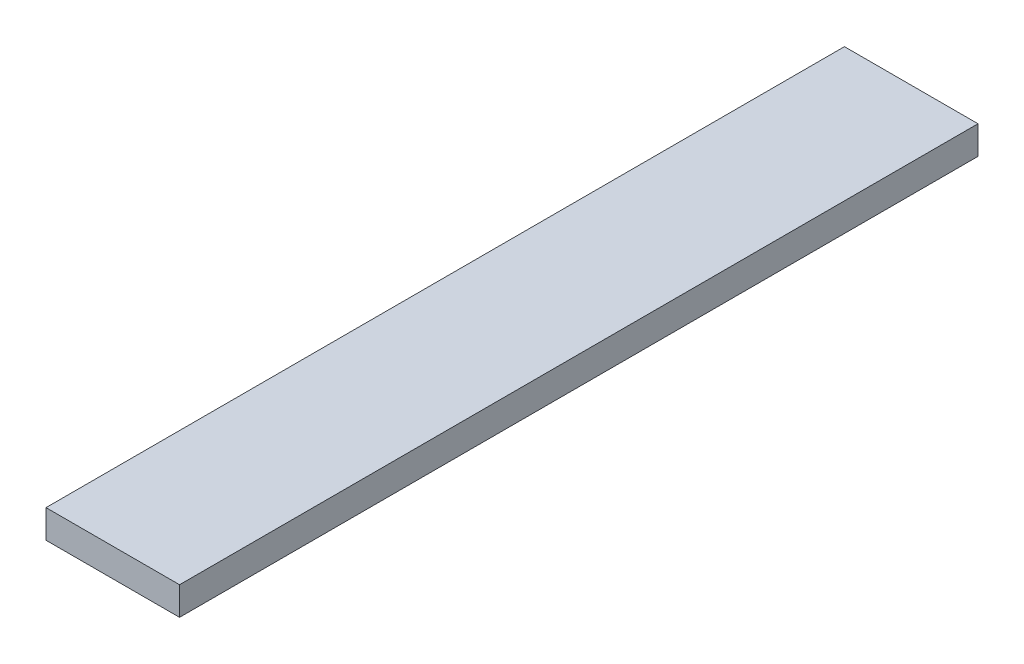
SolidWorks part; units mm, degrees
ref_plane "Front Plane" through (0, 0, 0) normal (0, 0, 1) x (1, 0, 0)
ref_plane "Top Plane" through (0, 0, 0) normal (0, 1, 0) x (1, 0, 0)
ref_plane "Right Plane" through (0, 0, 0) normal (1, 0, 0) x (0, 0, -1)
sketch "Sketch1" plane through (0, 0, 0) normal (0, 0, 1) x (1, 0, 0)
  line L0 (-10, 22.375) -> (-10, 19.2) construction
  line L1 (-10, 19.2) -> (-25, 19.2) construction
  line L2 (-25, 19.2) -> (-25, 22.375) construction
  line L3 (-25, 22.375) -> (-10, 22.375) construction
  line L4 (-10, 22.375) -> (-10, 19.2)
  line L5 (-10, 19.2) -> (-25, 19.2)
  line L6 (-25, 19.2) -> (-25, 22.375)
  line L7 (-25, 22.375) -> (-10, 22.375)
extrude "Boss-Extrude1" add sketch "Sketch1" against normal up to surface (89.675 mm away)
